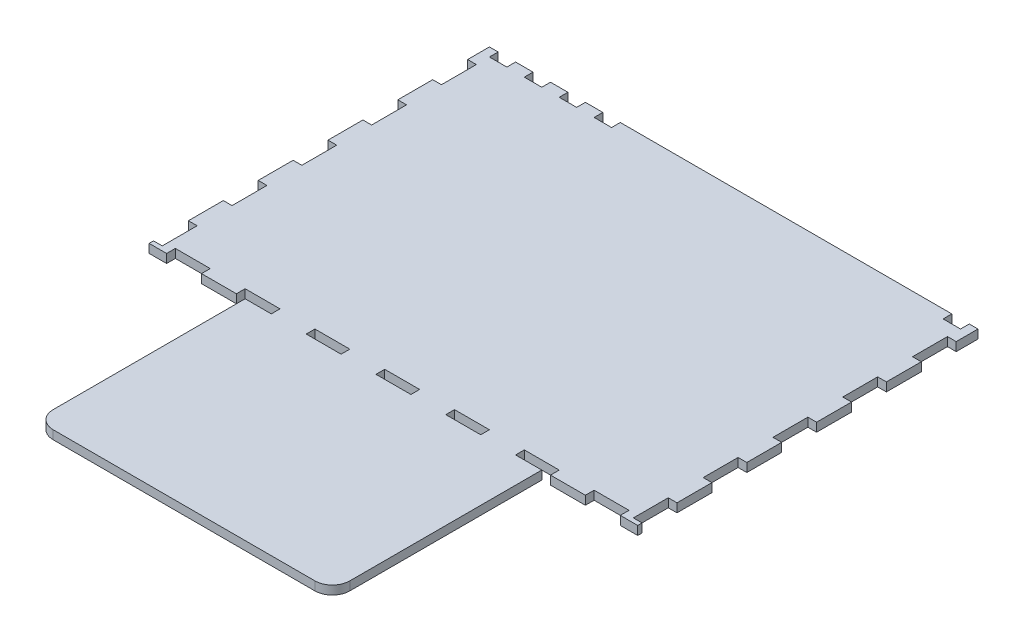
SolidWorks part; units mm, degrees
material "Pin"
ref_plane "Front" through (0, 0, 0) normal (0, 0, 1) x (1, 0, 0)
ref_plane "Top" through (0, 0, 0) normal (0, 1, 0) x (1, 0, 0)
ref_plane "Right" through (0, 0, 0) normal (1, 0, 0) x (0, 0, -1)
sketch "Esquisse1" plane through (0, 0, 0) normal (0, 1, 0) x (1, 0, 0)
  line L1 (-177.8, 184.15) -> (177.8, 184.15)
  line L2 (-177.8, 184.15) -> (-177.8, -184.15)
  line L3 (-177.8, -184.15) -> (177.8, -184.15)
  line L4 (177.8, 184.15) -> (177.8, -184.15)
  line L5 (-177.8, 184.15) -> (177.8, -184.15) construction
  line L6 (-177.8, -184.15) -> (177.8, 184.15) construction
  point P0 (0, 0)
  dimension "D1" = 368.3
  dimension "D2" = 355.6
extrude "Boss.-Extru.1" add sketch "Esquisse1" along normal blind 6.35
sketch "Esquisse2" plane through (0, 6.35, 0) normal (0, 1, 0) x (1, 0, 0)
  line L0 (177.8, -184.15) -> (177.8, 184.15) construction
  line L1 (177.8, -161.925) -> (171.45, -161.925)
  line L2 (177.8, -161.925) -> (177.8, -136.525)
  line L3 (177.8, -136.525) -> (171.45, -136.525)
  line L4 (171.45, -161.925) -> (171.45, -136.525)
  line L5 (-177.8, -184.15) -> (177.8, -184.15) construction
  dimension "D1" = 6.35
  dimension "D2" = 25.4
  dimension "D3" = 22.225
extrude "Enlèv. mat.-Extru.1" cut sketch "Esquisse2" against normal blind 6.35
pattern_linear "Répétition linéaire1" count 7 spacing 50.8 along (0, 0, -1) count 2 spacing 349.25 along (-1, 0, 0) of "Enlèv. mat.-Extru.1"
sketch "Esquisse3" plane through (0, 6.35, 0) normal (0, 1, 0) x (1, 0, 0)
  line L0 (-177.8, -184.15) -> (177.8, -184.15) construction
  line L1 (-165.1, -184.15) -> (-139.7, -184.15)
  line L2 (-165.1, -184.15) -> (-165.1, -177.8)
  line L3 (-165.1, -177.8) -> (-139.7, -177.8)
  line L4 (-139.7, -184.15) -> (-139.7, -177.8)
  line L5 (-177.8, -161.925) -> (-177.8, -184.15) construction
  dimension "D1" = 25.4
  dimension "D2" = 6.35
  dimension "D3" = 12.7
extrude "Enlèv. mat.-Extru.2" cut sketch "Esquisse3" against normal blind 6.35
pattern_linear "Répétition linéaire2" count 7 spacing 50.8 along (1, 0, 0) of "Enlèv. mat.-Extru.2"
sketch "Esquisse4" plane through (0, 6.35, 0) normal (0, 1, 0) x (1, 0, 0)
  line L0 (-177.8, -60.325) -> (-177.8, -85.725) construction
  line L1 (-165.1, -57.15) -> (-139.7, -57.15)
  line L2 (-165.1, -57.15) -> (-165.1, -63.5)
  line L3 (-165.1, -63.5) -> (-139.7, -63.5)
  line L4 (-139.7, -57.15) -> (-139.7, -63.5)
  line L5 (-139.7, -184.15) -> (-114.3, -184.15) construction
  dimension "D1" = 6.35
  dimension "D2" = 25.4
  dimension "D3" = 12.7
  dimension "D4" = 120.65
extrude "Enlèv. mat.-Extru.3" cut sketch "Esquisse4" against normal blind 6.35
pattern_linear "Répétition linéaire3" count 7 spacing 50.8 along (1, 0, 0) of "Enlèv. mat.-Extru.3"
sketch "Esquisse5" plane through (0, 6.35, 0) normal (0, 1, 0) x (1, 0, 0)
  line L0 (177.8, 184.15) -> (-177.8, 184.15) construction
  line L1 (-171.45, 184.15) -> (-158.75, 184.15)
  line L2 (-171.45, 184.15) -> (-171.45, 177.8)
  line L3 (-171.45, 177.8) -> (-158.75, 177.8)
  line L4 (-158.75, 184.15) -> (-158.75, 177.8)
  line L5 (-177.8, 184.15) -> (-177.8, 168.275) construction
  line L6 (177.8, 168.275) -> (177.8, 184.15) construction
  line L7 (171.45, 184.15) -> (158.75, 184.15)
  line L8 (171.45, 184.15) -> (171.45, 177.8)
  line L9 (171.45, 177.8) -> (158.75, 177.8)
  line L10 (158.75, 184.15) -> (158.75, 177.8)
  line L11 (-146.05, 184.15) -> (-133.35, 184.15)
  line L12 (-146.05, 184.15) -> (-146.05, 177.8)
  line L13 (-146.05, 177.8) -> (-133.35, 177.8)
  line L14 (-133.35, 184.15) -> (-133.35, 177.8)
  line L15 (-120.65, 184.15) -> (-107.95, 184.15)
  line L16 (-120.65, 184.15) -> (-120.65, 177.8)
  line L17 (-120.65, 177.8) -> (-107.95, 177.8)
  line L18 (-107.95, 184.15) -> (-107.95, 177.8)
  line L19 (-95.25, 184.15) -> (-82.55, 184.15)
  line L20 (-95.25, 184.15) -> (-95.25, 177.8)
  line L21 (-95.25, 177.8) -> (-82.55, 177.8)
  line L22 (-82.55, 184.15) -> (-82.55, 177.8)
  dimension "D1" = 6.35
  dimension "D2" = 12.7
  dimension "D3" = 6.35
  dimension "D4" = 6.35
  dimension "D5" = 12.7
  dimension "D6" = 6.35
  dimension "D7" = 4
extrude "Enlèv. mat.-Extru.4" cut sketch "Esquisse5" against normal blind 6.35
sketch "Sketch3" plane through (0, 6.35, 0) normal (0, 1, 0) x (1, 0, 0)
  line L0 (-177.8, -60.325) -> (-177.8, -85.725) construction
  line L1 (-177.8, -63.5) -> (177.7215, -63.5)
  line L2 (-177.8, -63.5) -> (-177.8, -278.4041)
  line L3 (-177.8, -278.4041) -> (177.7215, -278.4041)
  line L4 (177.7215, -63.5) -> (177.7215, -278.4041)
  line L5 (139.7, -63.5) -> (165.1, -63.5) construction
extrude "Boss-Extrude1" add sketch "Sketch3" against normal up to surface (6.35 mm away) up to face at (-12.7, 0, 11.7593)
sketch "Sketch1" plane through (0, 6.35, 0) normal (0, 1, 0) x (1, 0, 0)
  line L1 (-177.8, -60.325) -> (-177.8, -278.4041) construction
  line L3 (-95.25, -215.9) -> (95.25, -215.9)
  line L5 (177.8, -85.725) -> (177.8, -60.325) construction
  line L6 (107.95, -203.2) -> (107.95, -63.5)
  line L7 (-177.8, -278.4041) -> (177.7215, -278.4041) construction
  line L8 (88.9, -63.5) -> (114.3, -63.5) construction
  line L9 (-177.8, -63.5) -> (-177.8, -278.4041)
  line L10 (-177.8, -278.4041) -> (177.8, -278.4041)
  line L11 (177.8, -278.4041) -> (177.8, -63.5)
  line L12 (107.95, -63.5) -> (177.8, -63.5)
  line L13 (-107.95, -203.2) -> (-107.95, -63.5)
  line L14 (-114.3, -63.5) -> (-88.9, -63.5) construction
  line L15 (-107.95, -63.5) -> (-177.8, -63.5)
  arc A0 (95.25, -215.9) -> (107.95, -203.2) centre (95.25, -203.2) ccw
  arc A1 (-95.25, -215.9) -> (-107.95, -203.2) centre (-95.25, -203.2) cw
extrude "Cut-Extrude2" cut sketch "Sketch1" against normal through all
fillet "Fillet1" [suppressed] radius 12.7
